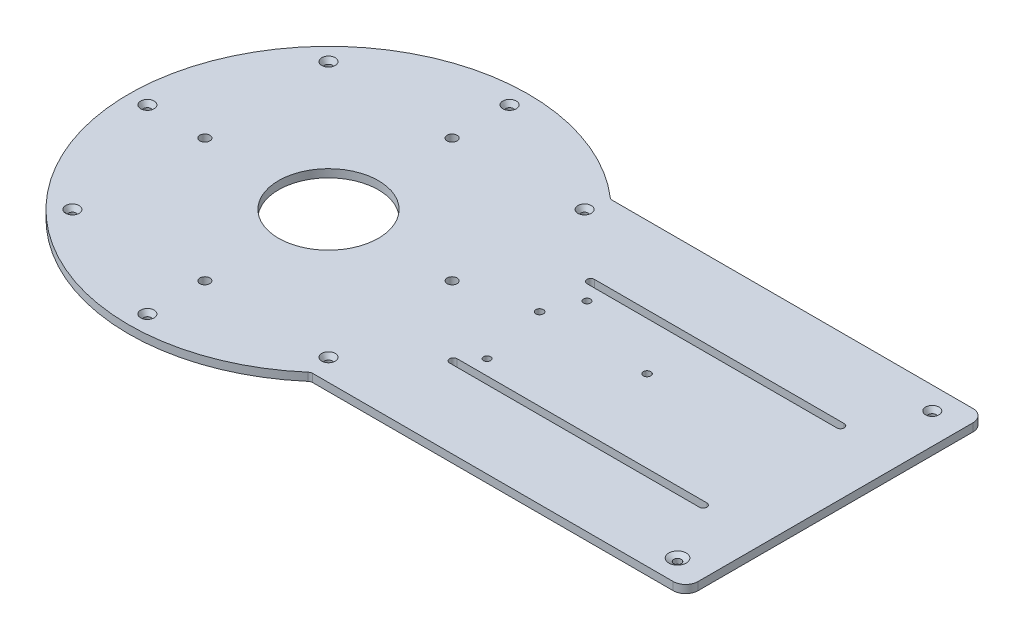
SolidWorks part; units mm, degrees
ref_plane "Front Plane" through (0, 0, 0) normal (0, 0, 1) x (1, 0, 0)
ref_plane "Top Plane" through (0, 0, 0) normal (0, 1, 0) x (1, 0, 0)
ref_plane "Right Plane" through (0, 0, 0) normal (1, 0, 0) x (0, 0, -1)
sketch "Sketch1" plane through (0, 0, 0) normal (0, 1, 0) x (1, 0, 0)
  line L0 (0, 0) -> (283, 0) construction
  line L1 (283, 0) -> (283, 60) construction
  line L2 (283, 0) -> (283, -60) construction
  line L3 (283, 55) -> (283, -55)
  line L4 (0, 0) -> (80, 0) construction
  line L5 (278, 60) -> (133.6656, 60)
  line L6 (278, -60) -> (133.6656, -60)
  line L10 (283, 60) -> (270.75, 60) construction
  line L11 (270.75, 60) -> (270.75, 51) construction
  line L12 (257.5, -27.5) -> (133.6656, -27.5) construction
  line L13 (257.5, 27.5) -> (133.6656, 27.5) construction
  line L15 (250.5, 27.5) -> (250.5, -27.5) construction
  line L16 (257.5, 34.5) -> (257.5, -34.5) construction
  line L19 (257.5, -34.5) -> (133.6656, -34.5) construction
  line L20 (257.5, 34.5) -> (133.6656, 34.5) construction
  line L21 (250.5, -27.5) -> (133.6656, -27.5) construction
  line L22 (250.5, 27.5) -> (133.6656, 27.5) construction
  line L23 (257.5, -27.5) -> (157.5, -27.5) construction
  line L24 (257.5, 27.5) -> (157.5, 27.5) construction
  line L25 (157.5, -29) -> (257.5, -29)
  line L26 (157.5, -26) -> (257.5, -26)
  line L27 (257.5, 26) -> (157.5, 26)
  line L28 (257.5, 29) -> (157.5, 29)
  line L29 (283, 60) -> (283, 20) construction
  line L30 (283, 20) -> (163.5, 20) construction
  line L31 (283, -60) -> (283, 6.8) construction
  line L32 (283, 6.8) -> (157.75, 6.8) construction
  line L33 (157.75, 6.8) -> (200.75, 6.8) construction
  arc A0 (132.3567, 60.4878) -> (132.3567, -60.4878) centre (80, 0) ccw
  circle A1 centre (80, 0) radius 20
  arc A2 (133.6656, -60) -> (132.3567, -60.4878) centre (133.6656, -62) ccw
  arc A3 (133.6656, 60) -> (132.3567, 60.4878) centre (133.6656, 62) cw
  circle A7 centre (7.5, 0) radius 1.5
  circle A8 centre (28.7348, 51.2652) radius 1.5
  circle A9 centre (80, 72.5) radius 1.5
  circle A10 centre (131.2652, 51.2652) radius 1.5
  circle A12 centre (131.2652, -51.2652) radius 1.5
  circle A13 centre (80, -72.5) radius 1.5
  circle A14 centre (28.7348, -51.2652) radius 1.5
  circle A15 centre (152.5, 0) radius 1.5 [skipped]
  circle A16 centre (80, 0) radius 49.5 construction
  circle A17 centre (30.5, 0) radius 2
  circle A21 centre (270.75, 51) radius 1.5
  circle A22 centre (270.75, -51) radius 1.5
  arc A23 (283, -55) -> (278, -60) centre (278, -55) cw
  arc A24 (283, 55) -> (278, 60) centre (278, 55) ccw
  arc A28 (250.5, 27.5) -> (250.5, 27.5) centre (250.5, 27.5) ccw
  arc A29 (250.5, -27.5) -> (250.5, -27.5) centre (250.5, -27.5) cw
  arc A30 (133.6656, -27.5) -> (111.0868, -35.9146) centre (133.6656, -62) ccw construction
  arc A31 (111.0868, 35.9146) -> (111.0868, -35.9146) centre (80, 0) ccw construction
  arc A32 (133.6656, 27.5) -> (111.0868, 35.9146) centre (133.6656, 62) cw construction
  arc A33 (257.5, -34.5) -> (257.5, -34.5) centre (257.5, -34.5) cw
  arc A37 (257.5, 34.5) -> (257.5, 34.5) centre (257.5, 34.5) ccw
  arc A38 (133.6656, -34.5) -> (115.668, -41.2073) centre (133.6656, -62) ccw construction
  arc A39 (115.668, 41.2073) -> (115.668, -41.2073) centre (80, 0) ccw construction
  arc A40 (133.6656, 34.5) -> (115.668, 41.2073) centre (133.6656, 62) cw construction
  arc A41 (257.5, -29) -> (257.5, -26) centre (257.5, -27.5) ccw
  arc A42 (257.5, 26) -> (257.5, 29) centre (257.5, 27.5) ccw
  arc A43 (157.5, -26) -> (157.5, -29) centre (157.5, -27.5) ccw
  arc A44 (157.5, 29) -> (157.5, 26) centre (157.5, 27.5) ccw
  circle A45 centre (163.5, 20) radius 1.4
  circle A46 centre (163.5, -20) radius 1.4
  circle A47 centre (157.75, 6.8) radius 1.5
  circle A48 centre (200.75, 6.8) radius 1.5
  circle A49 centre (80, 49.5) radius 2
  circle A50 centre (129.5, 0) radius 2
  circle A51 centre (80, -49.5) radius 2
  point P32 (80, 0)
  point P42 (79, -1)
  point P102 (80, 0)
  dimension "D5" = 2
  dimension "D7" = 8
  dimension "D8" = 4
  dimension "D9" = 9
  dimension "D11" = 5
  dimension "D16" = 100
  dimension "D19" = 119.5
  dimension "D22" = 43
  dimension "D23" = 30.5
  dimension "D1" = 283
  dimension "D2" = 60
  dimension "D3" = 60
  dimension "D4" = 80
  dimension "D6" = 7.5
  dimension "D10" = 12.25
  dimension "D13" = 32.5
  dimension "D15" = 25.5
  dimension "D17" = 100
  dimension "D18" = 40
  dimension "D20" = 53.2
  dimension "D21" = 125.25
  dimension "D12" = 32.5
  dimension "D14" = 25.5
extrude "Boss-Extrude1" add sketch "Sketch1" along normal blind 3.2
chamfer "Chamfer1" distance 1.2 angle 59 9 edges at (131.2652, 3.2, -49.7652) (7.5, 3.2, 1.5) (28.7348, 3.2, 52.7652) (80, 3.2, 74) (131.2652, 3.2, 52.7652) (270.75, 3.2, 52.5) (270.75, 3.2, -49.5) (80, 3.2, -71) (28.7348, 3.2, -49.7652)
